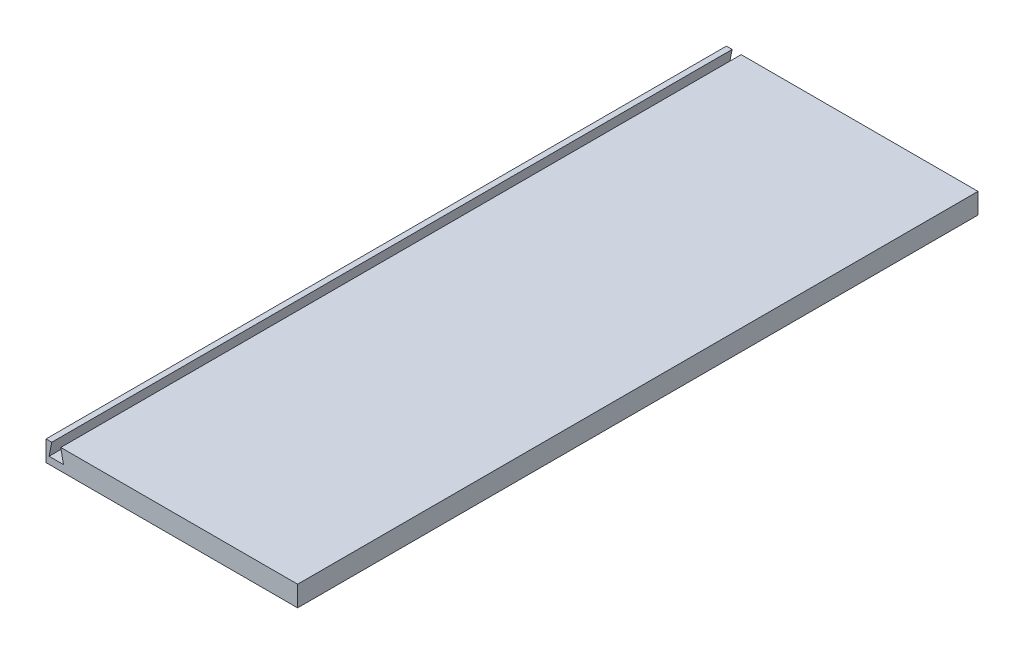
SolidWorks part; units mm, degrees
ref_plane "Front Plane" through (0, 0, 0) normal (0, 0, 1) x (1, 0, 0)
ref_plane "Top Plane" through (0, 0, 0) normal (0, 1, 0) x (1, 0, 0)
ref_plane "Right Plane" through (0, 0, 0) normal (1, 0, 0) x (0, 0, -1)
sketch "Sketch1" plane through (0, 0, 0) normal (0, 0, 1) x (1, 0, 0)
  line L1 (0, 0) -> (98, 0)
  line L2 (0, 0) -> (0, 8)
  line L3 (0, 8) -> (98, 8)
  line L4 (98, 0) -> (98, 8)
  dimension "D1" = 8
  dimension "D2" = 98
extrude "Boss-Extrude1" add sketch "Sketch1" against normal blind 265
sketch "Sketch2" plane through (0, 0, 0) normal (0, 0, 1) x (1, 0, 0)
  line L7 (2.245, 8) -> (1.195, 2.75)
  line L8 (1.195, 2.75) -> (6.805, 2.75)
  line L9 (6.805, 2.75) -> (5.755, 8)
  line L10 (2.245, 8) -> (5.755, 8)
  line L11 (0, 8) -> (0, 0) construction
  point P0 (4, 8)
  dimension "D1" = 4
  dimension "D2" = 3.5099
  dimension "D3" = 5.6099
  dimension "D4" = 5.25
  dimension "D5" = 2.245
extrude "Cut-Extrude2" cut sketch "Sketch2" against normal blind 265
